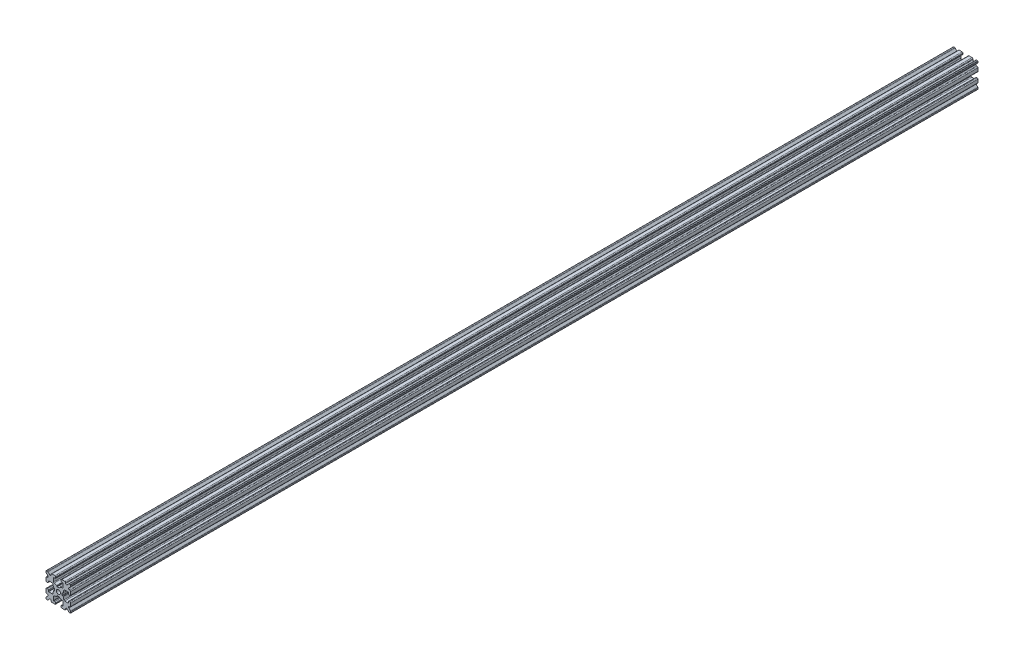
SolidWorks part; units mm, degrees
material "1060 Alloy"
ref_plane "Front Plane" through (0, 0, 0) normal (0, 0, 1) x (1, 0, 0)
ref_plane "Top Plane" through (0, 0, 0) normal (0, 1, 0) x (1, 0, 0)
ref_plane "Right Plane" through (0, 0, 0) normal (1, 0, 0) x (0, 0, -1)
sketch "Sketch1" plane through (0, 0, 0) normal (0, 0, 1) x (1, 0, 0)
  line L1 (-7.5, -7.5) -> (7.5, -7.5)
  line L2 (-7.5, -7.5) -> (-7.5, 7.5)
  line L3 (-7.5, 7.5) -> (7.5, 7.5)
  line L4 (7.5, -7.5) -> (7.5, 7.5)
  line L5 (-7.5, -7.5) -> (7.5, 7.5) construction
  line L6 (-7.5, 7.5) -> (7.5, -7.5) construction
  circle A0 centre (0, 0) radius 1.25
  point P0 (0, 0)
  dimension "D2" = 2.5
  dimension "D1" = 15
extrude "Boss-Extrude1" add sketch "Sketch1" along normal mid plane 550
fillet "Fillet1" radius 0.25 4 edges at (7.5, -7.5, 0) (-7.5, -7.5, 0) (7.5, 7.5, 0) (-7.5, 7.5, 0)
sketch "Sketch2" plane through (0, 0, 275) normal (0, 0, 1) x (1, 0, 0)
  line L0 (-7.5, 7.25) -> (-7.5, -7.25) construction
  line L1 (-7.5, 1.6) -> (-6.1, 1.6)
  line L2 (-7.5, 1.6) -> (-7.5, -1.6)
  line L3 (-7.5, -1.6) -> (-6.1, -1.6)
  line L4 (-6.1, 1.6) -> (-6.1, 2.9)
  line L5 (0, 0) -> (-12.1036, 0) construction
  line L6 (-6.1, -2.9) -> (-3.4, -2.9)
  line L7 (0, 0) -> (-7.25, 7.25) construction
  line L8 (-6.1, 2.9) -> (-3.4, 2.9)
  line L9 (-3.4, -2.9) -> (-3.4, 2.9)
  line L10 (55, 0) -> (-55, 0) construction
  line L11 (-6.1, -2.9) -> (-6.1, -1.6)
  line L12 (2.9, 6.1) -> (1.6, 6.1)
  line L13 (2.9, 3.4) -> (-2.9, 3.4)
  line L14 (-2.9, 6.1) -> (-2.9, 3.4)
  line L15 (2.9, 6.1) -> (2.9, 3.4)
  line L16 (-1.6, 6.1) -> (-2.9, 6.1)
  line L17 (1.6, 7.5) -> (1.6, 6.1)
  line L18 (-1.6, 7.5) -> (1.6, 7.5)
  line L19 (-1.6, 7.5) -> (-1.6, 6.1)
  line L20 (-1.6, -7.5) -> (-1.6, -6.1)
  line L21 (-1.6, -7.5) -> (1.6, -7.5)
  line L22 (1.6, -7.5) -> (1.6, -6.1)
  line L23 (-1.6, -6.1) -> (-2.9, -6.1)
  line L24 (2.9, -6.1) -> (2.9, -3.4)
  line L25 (-2.9, -6.1) -> (-2.9, -3.4)
  line L26 (2.9, -3.4) -> (-2.9, -3.4)
  line L27 (2.9, -6.1) -> (1.6, -6.1)
  line L28 (6.1, -2.9) -> (6.1, -1.6)
  line L29 (3.4, -2.9) -> (3.4, 2.9)
  line L30 (6.1, 2.9) -> (3.4, 2.9)
  line L31 (6.1, -2.9) -> (3.4, -2.9)
  line L32 (6.1, 1.6) -> (6.1, 2.9)
  line L33 (7.5, -1.6) -> (6.1, -1.6)
  line L34 (7.5, 1.6) -> (7.5, -1.6)
  line L35 (7.5, 1.6) -> (6.1, 1.6)
  dimension "D1" = 3.2
  dimension "D2" = 5.8
  dimension "D3" = 1.4
  dimension "D4" = 2.7
extrude "Cut-Extrude1" cut sketch "Sketch2" against normal through all
sketch "Sketch4" plane through (0, 0, 275) normal (0, 0, 1) x (1, 0, 0)
  line L0 (-3.4, 2.9) -> (-2.75, 0)
  line L1 (55, 0) -> (-55, 0) construction
  line L2 (-2.75, 0) -> (-3.4, -2.9)
  line L3 (-3.4, -2.9) -> (-3.4, 2.9) construction
  line L4 (-3.4, 2.9) -> (-3.4, -2.9)
  line L5 (-2.9, 3.4) -> (0, 2.75)
  line L6 (0, 2.75) -> (2.9, 3.4)
  line L7 (2.9, 3.4) -> (-2.9, 3.4)
  line L8 (3.4, 2.9) -> (2.75, 0)
  line L9 (2.75, 0) -> (3.4, -2.9)
  line L10 (3.4, -2.9) -> (3.4, 2.9)
  line L11 (-2.9, -3.4) -> (0, -2.75)
  line L12 (0, -2.75) -> (2.9, -3.4)
  line L13 (2.9, -3.4) -> (-2.9, -3.4)
  circle A2 centre (0, 0) radius 2.75
  circle A3 centre (0, 0) radius 2.75 construction
  dimension "D1" = 1.5
extrude "Cut-Extrude3" cut sketch "Sketch4" against normal through all
fillet "Fillet3" radius 0.5 16 edges at (-6.1, -1.6, 0) (-7.5, -1.6, 0) (-6.1, 1.6, 0) (-7.5, 1.6, 0) (-1.6, -7.5, 0) (-1.6, -6.1, 0) (1.6, -7.5, 0) (1.6, -6.1, 0) (6.1, -1.6, 0) (7.5, -1.6, 0) (7.5, 1.6, 0) (6.1, 1.6, 0) (1.6, 7.5, 0) (1.6, 6.1, 0) (-1.6, 7.5, 0) (-1.6, 6.1, 0)
fillet "Fillet4" radius 0.5 8 edges at (-3.4, 2.9, 0) (-3.4, -2.9, 0) (2.9, -3.4, 0) (-2.9, -3.4, 0) (3.4, -2.9, 0) (3.4, 2.9, 0) (-2.9, 3.4, 0) (2.9, 3.4, 0)
fillet "Fillet5" radius 3 4 edges at (0, -2.75, 0) (2.75, 0, 0) (-2.75, 0, 0) (0, 2.75, 0)
fillet "Fillet6" radius 0.2 8 edges at (-2.9, -6.1, 0) (2.9, -6.1, 0) (6.1, -2.9, 0) (6.1, 2.9, 0) (2.9, 6.1, 0) (-2.9, 6.1, 0) (-6.1, -2.9, 0) (-6.1, 2.9, 0)
sketch "Sketch5" plane through (0, 0, 275) normal (0, 0, 1) x (1, 0, 0)
  line L0 (0, 0) -> (-7.25, 7.25) construction
  line L1 (-7.5, 6.4393) -> (-5.4607, 4.4)
  line L2 (-6.4393, 7.5) -> (-4.4, 5.4607)
  line L3 (-7.5, 4.4) -> (-5.4607, 4.4)
  line L4 (-3.8003, 2.9) -> (-5.9, 2.9) construction
  line L5 (0, 0) -> (-12.1819, 0) construction
  line L6 (-4.4, 7.5) -> (-4.4, 5.4607)
  line L7 (-2.9, 5.9) -> (-2.9, 3.8003) construction
  line L8 (-7.5, 6.4393) -> (-7.5, 4.4)
  line L9 (-7.5, 7.25) -> (-7.5, 2.1) construction
  line L10 (2.1, -7.5) -> (7.25, -7.5) construction
  line L11 (7.5, -7.25) -> (7.5, -2.1) construction
  line L12 (7.25, 7.5) -> (2.1, 7.5) construction
  line L13 (-2.1, 7.5) -> (-7.25, 7.5) construction
  line L14 (-4.4, 7.5) -> (-6.4393, 7.5)
  line L16 (55, 0) -> (-55, 0) construction
  line L17 (0, 0) -> (0, 10.993) construction
  line L18 (0, -54.6431) -> (0, 54.6431) construction
  line L20 (4.4, 7.5) -> (6.4393, 7.5)
  line L22 (7.5, 6.4393) -> (7.5, 4.4)
  line L23 (4.4, 7.5) -> (4.4, 5.4607)
  line L24 (7.5, 4.4) -> (5.4607, 4.4)
  line L25 (6.4393, 7.5) -> (4.4, 5.4607)
  line L26 (7.5, 6.4393) -> (5.4607, 4.4)
  line L27 (7.5, -6.4393) -> (5.4607, -4.4)
  line L28 (6.4393, -7.5) -> (4.4, -5.4607)
  line L29 (7.5, -4.4) -> (5.4607, -4.4)
  line L30 (4.4, -7.5) -> (4.4, -5.4607)
  line L31 (7.5, -6.4393) -> (7.5, -4.4)
  line L33 (4.4, -7.5) -> (6.4393, -7.5)
  line L36 (-4.4, -7.5) -> (-6.4393, -7.5)
  line L38 (-7.5, -6.4393) -> (-7.5, -4.4)
  line L39 (-4.4, -7.5) -> (-4.4, -5.4607)
  line L40 (-7.5, -4.4) -> (-5.4607, -4.4)
  line L41 (-6.4393, -7.5) -> (-4.4, -5.4607)
  line L42 (-7.5, -6.4393) -> (-5.4607, -4.4)
  dimension "D1" = 1.5
  dimension "D2" = 1.5
  dimension "D3" = 1.5
extrude "Cut-Extrude4" cut sketch "Sketch5" against normal through all
fillet "Fillet8" radius 0.5 24 edges at (-5.4607, 4.4, 0) (-7.5, 4.4, 0) (-5.4607, -4.4, 0) (-7.5, -4.4, 0) (-4.4, -7.5, 0) (-4.4, -5.4607, 0) (4.4, -7.5, 0) (4.4, -5.4607, 0) (5.4607, -4.4, 0) (7.5, -4.4, 0) (7.5, 4.4, 0) (5.4607, 4.4, 0) (4.4, 5.4607, 0) (4.4, 7.5, 0) (-4.4, 5.4607, 0) (-4.4, 7.5, 0) (-6.4393, 7.5, 0) (-7.5, 6.4393, 0) (6.4393, 7.5, 0) (7.5, 6.4393, 0) (6.4393, -7.5, 0) (7.5, -6.4393, 0) (-6.4393, -7.5, 0) (-7.5, -6.4393, 0)
sketch "Sketch6" plane through (0, 0, 275) normal (0, 0, 1) x (1, 0, 0)
  line L0 (0, 0) -> (0, 11.013) construction
  line L1 (0.6561, 2.8971) -> (2.1235, 2.8971) construction
  line L2 (0, -54.6431) -> (0, 54.6431) construction
  line L3 (0, 0) -> (7.25, 7.25) construction
  line L4 (7.5, 0.8255) -> (7.5, -0.8255)
  line L5 (2.3471, 0.8255) -> (7.5, 0.8255)
  line L6 (0, 0) -> (12.4016, 0) construction
  line L7 (0.8255, -7.5) -> (-0.8255, -7.5)
  line L8 (2.3471, -0.8255) -> (2.3471, 0.8255)
  line L9 (0.8255, -2.3471) -> (0.8255, -7.5)
  line L10 (7.5, -0.8255) -> (2.3471, -0.8255)
  line L11 (-7.5, -0.8255) -> (-2.3471, -0.8255)
  line L12 (-2.3471, -0.8255) -> (-2.3471, 0.8255)
  line L13 (-0.8255, -2.3471) -> (0.8255, -2.3471)
  line L14 (-0.8255, 7.5) -> (-0.8255, 2.3471)
  line L15 (-0.8255, 2.3471) -> (0.8255, 2.3471)
  line L16 (-0.8255, -7.5) -> (-0.8255, -2.3471)
  line L17 (0.8255, 2.3471) -> (0.8255, 7.5)
  line L18 (0.8255, 7.5) -> (-0.8255, 7.5)
  line L19 (3.9, 7.5) -> (2.1, 7.5) construction
  line L20 (-2.3471, 0.8255) -> (-7.5, 0.8255)
  line L21 (-7.5, 0.8255) -> (-7.5, -0.8255)
  point P5 (0, -2.5973)
  point P7 (0, 2.5973)
  dimension "D3" = 0.55
  dimension "D1" = 1.651
extrude "Cut-Extrude5" cut sketch "Sketch6" against normal through all
fillet "Fillet10" radius 0.2 16 edges at (-2.935, 0.8255, 0) (-2.935, -0.8255, 0) (2.935, -0.8255, 0) (2.935, 0.8255, 0) (0.8255, 2.935, 0) (-0.8255, 2.935, 0) (-2.3471, 0.8255, 0) (-2.3471, -0.8255, 0) (0.8255, 2.3471, 0) (-0.8255, 2.3471, 0) (2.3471, 0.8255, 0) (2.3471, -0.8255, 0) (0.8255, -2.935, 0) (0.8255, -2.3471, 0) (-0.8255, -2.3471, 0) (-0.8255, -2.935, 0)
